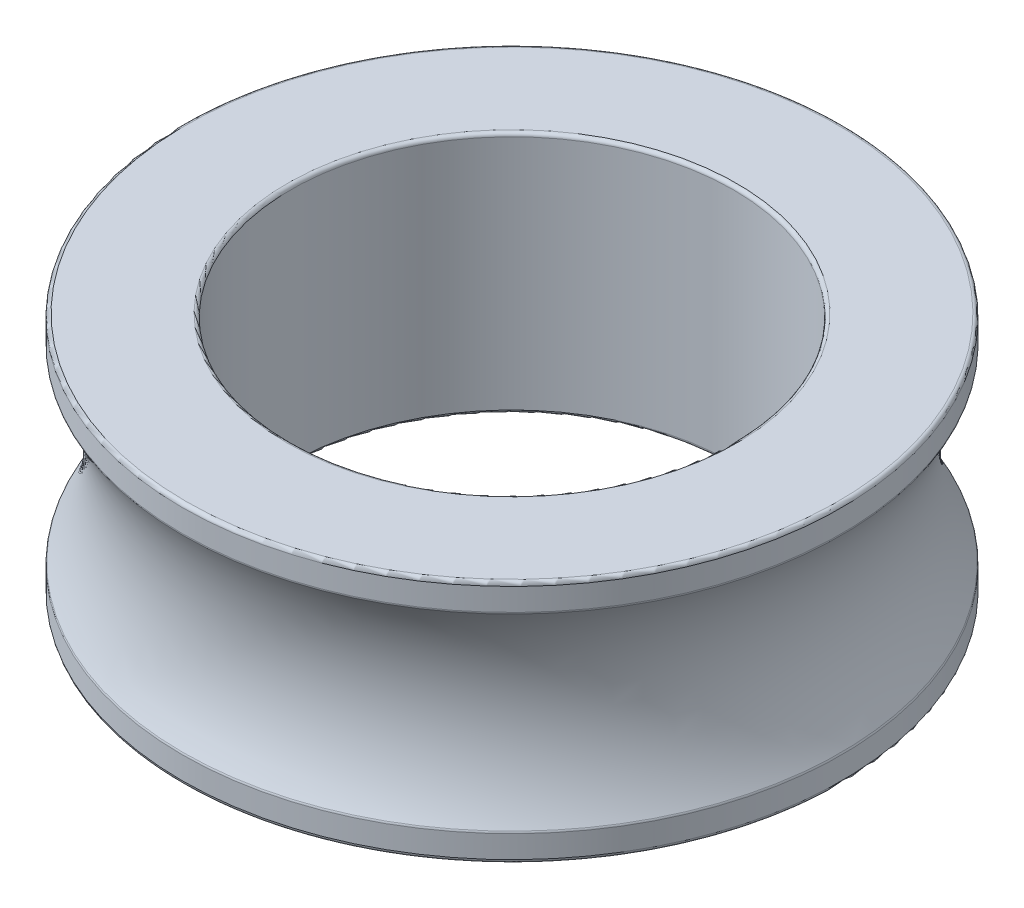
SolidWorks part; units mm, degrees
ref_plane "Front Plane" through (0, 0, 0) normal (0, 0, 1) x (1, 0, 0)
ref_plane "Top Plane" through (0, 0, 0) normal (0, 1, 0) x (1, 0, 0)
ref_plane "Right Plane" through (0, 0, 0) normal (1, 0, 0) x (0, 0, -1)
sketch "Sketch1" plane through (0, 0, 0) normal (0, 0, 1) x (1, 0, 0)
  line L0 (9.125, 6) -> (9.125, 6.75)
  line L1 (6.125, 0) -> (9.125, 0)
  line L2 (6.125, 0) -> (6.125, 6.75)
  line L3 (6.125, 6.75) -> (9.125, 6.75)
  line L4 (9.125, 0) -> (9.125, 0.75)
  line L5 (0, 0) -> (0, 4.9497) construction
  arc A0 (9.125, 6) -> (9.125, 0.75) centre (13.3805, 3.375) ccw
  dimension "D4" = 5
  dimension "D1" = 6.75
  dimension "D2" = 6.125
  dimension "D3" = 3
  dimension "D5" = 0.75
  dimension "D6" = 0.75
revolve "Revolve1" add sketch "Sketch1" angle 360 about L5
fillet "Fillet1" radius 0.1 6 edges at (0, 0, -6.125) (0, 0, -9.125) (0, 0.75, -9.125) (0, 6, -9.125) (0, 6.75, -9.125) (0, 6.75, -6.125)
